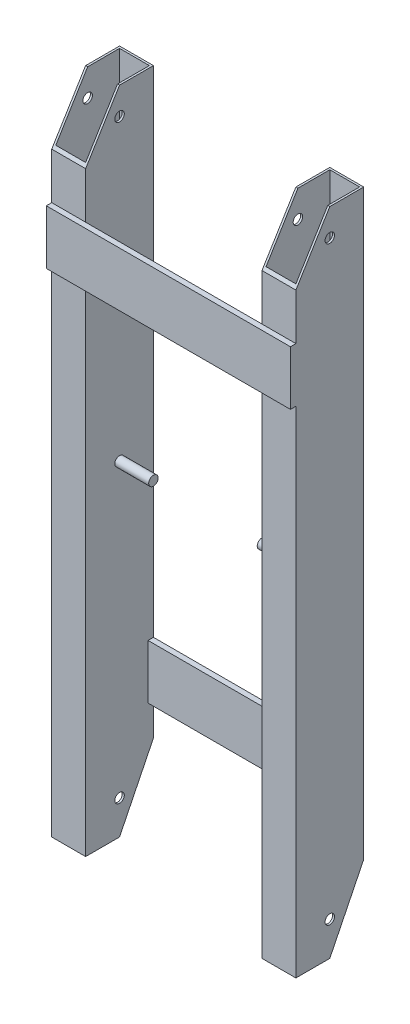
SolidWorks part; units mm, degrees
material "1060 Alloy"
ref_plane "Front Plane" through (0, 0, 0) normal (0, 0, 1) x (1, 0, 0)
ref_plane "Top Plane" through (0, 0, 0) normal (0, 1, 0) x (1, 0, 0)
ref_plane "Right Plane" through (0, 0, 0) normal (1, 0, 0) x (0, 0, -1)
sketch "Sketch1" plane through (0, 0, 0) normal (0, 0, 1) x (1, 0, 0)
  line L0 (-173.1848, -812) -> (-173.1848, -1292)
  line L1 (-328.1848, -812) -> (-303.1848, -812)
  line L2 (-328.1848, -812) -> (-328.1848, -1292)
  line L3 (-328.1848, -1292) -> (-303.1848, -1292)
  line L4 (-303.1848, -812) -> (-303.1848, -1292)
  line L5 (-148.1848, -812) -> (-148.1848, -1292)
  line L6 (-173.1848, -812) -> (-148.1848, -812)
  line L7 (-173.1848, -1292) -> (-148.1848, -1292)
  dimension "D1" = 480
  dimension "D2" = 25
  dimension "D4" = 130
  dimension "D3" = 2
extrude "Boss-Extrude1" add sketch "Sketch1" along normal blind 50
shell "Shell1" thickness 1.5
shell "Shell2" thickness 1.5
sketch "Sketch2" plane through (0, 0, 0) normal (0, 0, 1) x (1, 0, 0)
  line L0 (-328.1848, -812) -> (-328.1848, -1292) construction
  line L1 (-328.1848, -1177) -> (-148.1848, -1177)
  line L2 (-328.1848, -1177) -> (-328.1848, -1217)
  line L3 (-328.1848, -1217) -> (-148.1848, -1217)
  line L4 (-148.1848, -1177) -> (-148.1848, -1217)
  line L5 (-148.1848, -1292) -> (-148.1848, -812) construction
  line L6 (-328.1848, -1292) -> (-303.1848, -1292) construction
  dimension "D1" = 75
  dimension "D2" = 40
extrude "Boss-Extrude2" add sketch "Sketch2" along normal blind 4
sketch "Sketch3" plane through (0, 0, 50) normal (0, 0, 1) x (1, 0, 0)
  line L0 (-328.1848, -812) -> (-328.1848, -1292) construction
  line L1 (-328.1848, -927) -> (-148.1848, -927)
  line L2 (-328.1848, -927) -> (-328.1848, -887)
  line L3 (-328.1848, -887) -> (-148.1848, -887)
  line L4 (-148.1848, -927) -> (-148.1848, -887)
  line L5 (-148.1848, -1292) -> (-148.1848, -812) construction
  line L6 (-303.1848, -812) -> (-328.1848, -812) construction
  dimension "D1" = 115
  dimension "D2" = 40
extrude "Boss-Extrude3" add sketch "Sketch3" along normal blind 4
sketch "Sketch4" plane through (-328.1848, 0, 0) normal (-1, 0, 0) x (0, 0, 1)
  line L0 (50, -1292) -> (0, -1292) construction
  line L1 (0, -812) -> (0, -1292) construction
  circle A0 centre (25, -1267) radius 3.5
  circle A1 centre (25, -832) radius 3.5
  dimension "D3" = 7
  dimension "D1" = 25
  dimension "D2" = 25
  dimension "D4" = 2
extrude "Cut-Extrude1" cut sketch "Sketch4" against normal through all both and the other way through all
sketch "Sketch5" plane through (-303.1848, 0, 0) normal (1, 0, 0) x (0, 0, -1)
  line L0 (-50, -1292) -> (-50, -927) construction
  line L2 (-50, -812) -> (0, -812) construction
  circle A0 centre (-25, -1052) radius 3.5
  dimension "D1" = 7
  dimension "D2" = 25
  dimension "D3" = 240
extrude "Boss-Extrude4" add sketch "Sketch5" along normal blind 25
sketch "Sketch6" plane through (-173.1848, 0, 0) normal (-1, 0, 0) x (0, 0, 1)
  line L0 (50, -812) -> (0, -812) construction
  line L2 (50, -927) -> (50, -1292) construction
  circle A0 centre (25, -1052) radius 3.5
  dimension "D1" = 7
  dimension "D2" = 240
  dimension "D3" = 25
extrude "Boss-Extrude5" add sketch "Sketch6" along normal blind 25
sketch "Sketch11" plane through (-328.1848, 0, 0) normal (-1, 0, 0) x (0, 0, 1)
  line L0 (25, -812) -> (50, -852.8248)
  line L1 (50, -812) -> (0, -812) construction
  line L2 (50, -812) -> (50, -887) construction
  line L3 (50, -852.8248) -> (50, -812)
  line L4 (50, -812) -> (25, -812)
extrude "Cut-Extrude6" cut sketch "Sketch11" against normal through all both and the other way through all
sketch "Sketch12" plane through (-328.1848, 0, 0) normal (-1, 0, 0) x (0, 0, 1)
  line L0 (25, -1292) -> (0, -1241.2849)
  line L1 (50, -1292) -> (0, -1292) construction
  line L2 (0, -812) -> (0, -1292) construction
  line L3 (0, -1241.2849) -> (0, -1292)
  line L4 (0, -1292) -> (25, -1292)
extrude "Cut-Extrude7" cut sketch "Sketch12" against normal through all both and the other way through all
